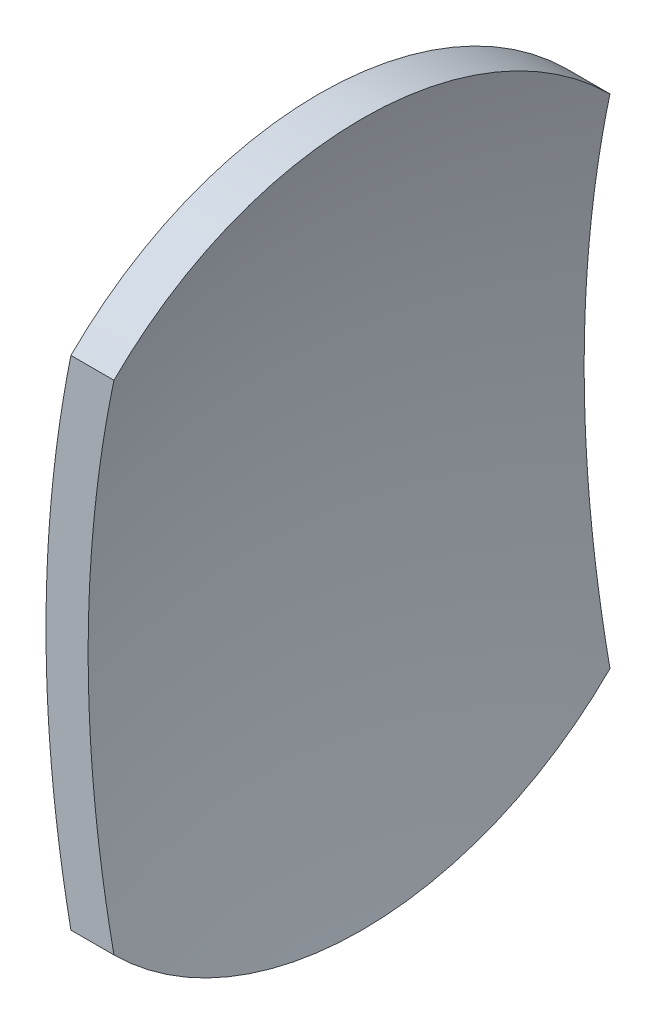
SolidWorks part; units mm, degrees
ref_plane "前视基准面" through (0, 0, 0) normal (0, 0, 1) x (1, 0, 0)
ref_plane "上视基准面" through (0, 0, 0) normal (0, 1, 0) x (1, 0, 0)
ref_plane "右视基准面" through (0, 0, 0) normal (1, 0, 0) x (0, 0, -1)
other "Configuration Table"
sketch "草图2" plane through (0, 0, 0) normal (0, 0, 1) x (1, 0, 0)
  line L0 (0, 0) -> (-60, 0) construction
  line L1 (-59.6238, 17) -> (-57.5413, 17)
  line L2 (-60, 0) -> (-62, 0)
  arc A0 (-57.5413, 17) -> (-60, 0) centre (0, 0) ccw
  arc A1 (-59.6238, 17) -> (-62, 0) centre (0, 0) ccw
  dimension "D1" = 120
  dimension "D2" = 2
  dimension "D3" = 17
revolve "旋转1" add sketch "草图2" angle 360 about L0
sketch "草图3" plane through (0, 0, 0) normal (1, 0, 0) x (0, 0, -1)
  line L0 (-12, 12.0416) -> (-12, -12.0416)
  line L1 (12, 12.0416) -> (12, -12.0416)
  circle A0 centre (0, 0) radius 17 construction
  arc A1 (12, -12.0416) -> (12, 12.0416) centre (0, 0) ccw
  circle A2 centre (0, 0) radius 17
  arc A3 (-12, 12.0416) -> (-12, -12.0416) centre (0, 0) ccw
  dimension "D1" = 0
  dimension "D2" = 12
  dimension "D3" = 12
extrude "切除-拉伸1" cut sketch "草图3" against normal up to next
